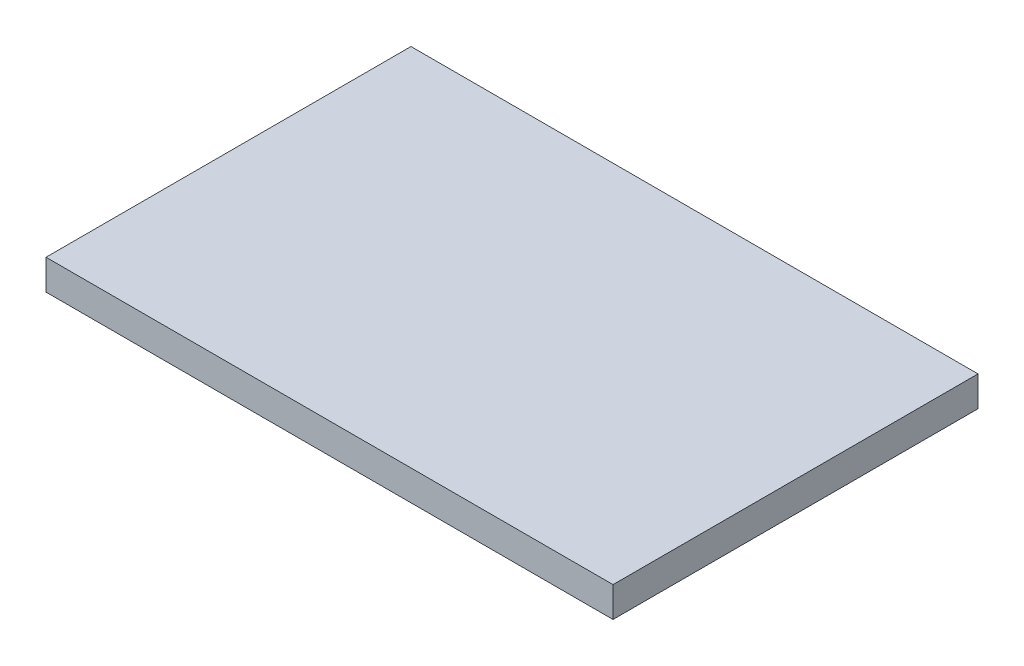
SolidWorks part; units mm, degrees
ref_plane "Front Plane" through (0, 0, 0) normal (0, 0, 1) x (1, 0, 0)
ref_plane "Top Plane" through (0, 0, 0) normal (0, 1, 0) x (1, 0, 0)
ref_plane "Right Plane" through (0, 0, 0) normal (1, 0, 0) x (0, 0, -1)
sketch "Sketch1" plane through (0, 0, 0) normal (0, 1, 0) x (1, 0, 0)
  line L1 (-23.8375, -15.3434) -> (23.8375, -15.3434)
  line L2 (-23.8375, -15.3434) -> (-23.8375, 15.3434)
  line L3 (-23.8375, 15.3434) -> (23.8375, 15.3434)
  line L4 (23.8375, -15.3434) -> (23.8375, 15.3434)
  line L5 (-23.8375, -15.3434) -> (23.8375, 15.3434) construction
  line L6 (-23.8375, 15.3434) -> (23.8375, -15.3434) construction
  point P0 (0, 0)
extrude "Boss-Extrude1" add sketch "Sketch1" along normal blind 2.54
